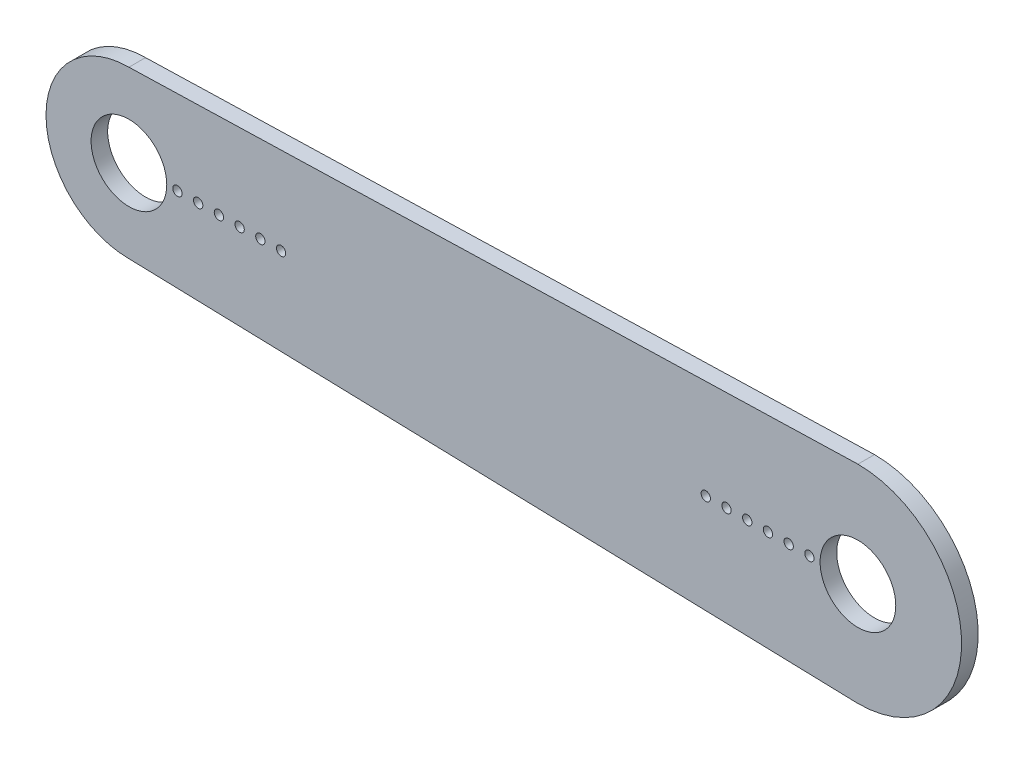
SolidWorks part; units mm, degrees
ref_plane "Plano frontal" through (0, 0, 0) normal (0, 0, 1) x (1, 0, 0)
ref_plane "Plano superior" through (0, 0, 0) normal (0, 1, 0) x (1, 0, 0)
ref_plane "Plano direito" through (0, 0, 0) normal (1, 0, 0) x (0, 0, -1)
sketch "Esboço1" plane through (0, 0, 0) normal (0, 0, 1) x (1, 0, 0)
  line L0 (0, 0) -> (-70.33, 0) construction
  line L1 (-70.33, 8) -> (0, 10)
  line L2 (0, -10) -> (-70.33, -8)
  circle A0 centre (0, 0) radius 3.65
  circle A1 centre (-70.33, 0) radius 3.65
  arc A2 (-70.33, 8) -> (-70.33, -8) centre (-70.33, 0) ccw
  arc A3 (-0.5683, -9.9838) -> (-0.5683, 9.9838) centre (0, 0) ccw
  dimension "D1" = 7.3
  dimension "D2" = 7.3
  dimension "D4" = 8
  dimension "D5" = 10
  dimension "D3" = 70.33
extrude "Ressalto-extrusão1" add sketch "Esboço1" along normal blind 1.6
sketch "Esboço3" plane through (0, 0, 1.6) normal (0, 0, 1) x (1, 0, 0)
  line L0 (-70.33, 0) -> (-65.65, 0) construction
  line L1 (0, 0) -> (-4.68, 0) construction
  circle A0 centre (-65.65, 0) radius 0.45
  circle A1 centre (-4.68, 0) radius 0.45
  circle A2 centre (-6.68, 0) radius 0.45
  circle A3 centre (-8.68, 0) radius 0.45
  circle A4 centre (-10.68, 0) radius 0.45
  circle A5 centre (-12.68, 0) radius 0.45
  circle A6 centre (-14.68, 0) radius 0.45
  circle A7 centre (-63.65, 0) radius 0.45
  circle A8 centre (-61.65, 0) radius 0.45
  circle A9 centre (-59.65, 0) radius 0.45
  circle A10 centre (-57.65, 0) radius 0.45
  circle A11 centre (-55.65, 0) radius 0.45
  dimension "D1" = 6
  dimension "D2" = 6
extrude "Corte-extrusão2" cut sketch "Esboço3" against normal up to next
